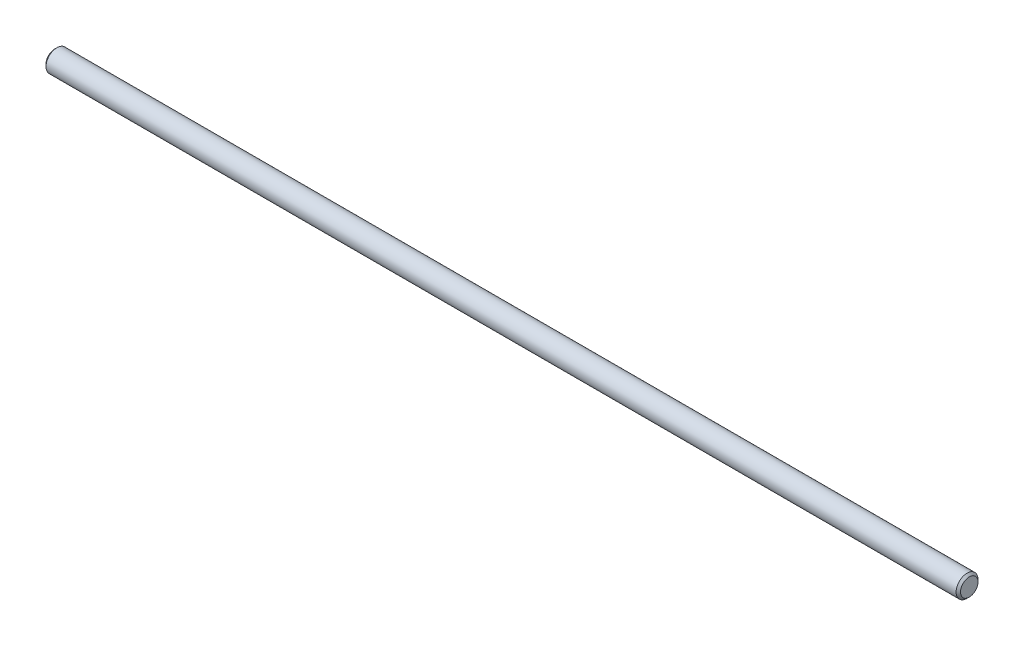
SolidWorks part; units mm, degrees
ref_plane "Front Plane" through (0, 0, 0) normal (0, 0, 1) x (1, 0, 0)
ref_plane "Top Plane" through (0, 0, 0) normal (0, 1, 0) x (1, 0, 0)
ref_plane "Right Plane" through (0, 0, 0) normal (1, 0, 0) x (0, 0, -1)
sketch "Sketch1" plane through (0, 0, 0) normal (1, 0, 0) x (0, 0, -1)
  circle A0 centre (0, 0) radius 5
  dimension "D1" = 10
extrude "Boss-Extrude1" add sketch "Sketch1" along normal mid plane 418
chamfer "Chamfer1" distance 1 angle 45 2 edges at (209, 0, -5) (-209, 0, -5)
